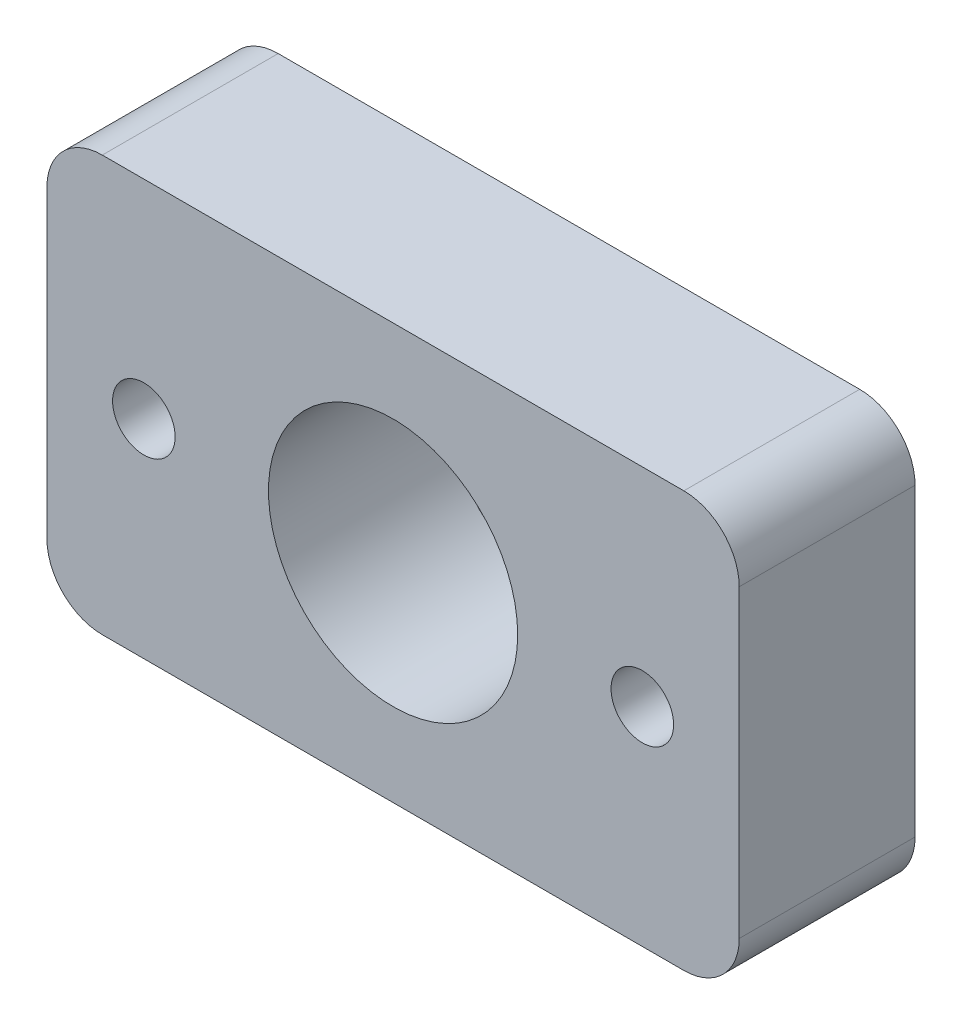
SolidWorks part; units mm, degrees
ref_plane "Front Plane" through (0, 0, 0) normal (0, 0, 1) x (1, 0, 0)
ref_plane "Top Plane" through (0, 0, 0) normal (0, 1, 0) x (1, 0, 0)
ref_plane "Right Plane" through (0, 0, 0) normal (1, 0, 0) x (0, 0, -1)
sketch "Sketch1" plane through (0, 0, 0) normal (0, 0, 1) x (1, 0, 0)
  line L1 (0, 0) -> (25, 0)
  line L2 (0, 0) -> (0, -15)
  line L3 (0, -15) -> (25, -15)
  line L4 (25, 0) -> (25, -15)
  circle A0 centre (12.5, -7.5) radius 4.5
  circle A1 centre (3.5, -7.5) radius 1.1303
  circle A2 centre (21.5, -7.5) radius 1.1303
  circle A3 centre (3.5, -7.5) radius 2.3241 construction
  point P7 (12.5, 0)
  point P9 (25, -7.5)
  dimension "D1" = 9
  dimension "D3" = 2.2606
  dimension "D7" = 4.6482
  dimension "D2" = 25
  dimension "D4" = 18
  dimension "D5" = 3.5
  dimension "D6" = 15
extrude "Boss-Extrude1" add sketch "Sketch1" along normal blind 6.35
hole_wizard "#4-40 Tapped Hole1" positions "3DSketch1" profile "Sketch2" tap size "#4-40" standard "ANSI Inch" end condition through all
sketch3d "3DSketch1"
  line L0 (21.5, -7.5, 6.35) -> (21.5, -7.5, 0) construction
  line L1 (3.5, -7.5, 6.35) -> (3.5, -7.5, 0) construction
  point P0 (21.5, -7.5, 6.35)
  point P4 (3.5, -7.5, 6.35)
sketch "Sketch2" plane through (21.5, -7.5, 6.35) normal (1, 0, 0) x (0, -1, 0)
  line L0 (0, 0) -> (0, 6.35)
  line L1 (0, 6.35) -> (1.1303, 6.35)
  line L2 (1.1303, 6.35) -> (1.1303, 0)
  line L5 (1.1303, 0) -> (0, 0)
  line L11 (0, -6.35) -> (0, 107.95) construction
  dimension "Thru Tap Drill Dia." = 2.2606
  dimension "Thru Tap Drill Depth" = 6.35
cosmetic thread "Hole Thread1" parameters "D2"=2.8448
cosmetic thread "Hole Thread2" parameters "D2"=2.8448
fillet "Fillet1" radius 2 4 edges at (0, -15, 3.175) (0, 0, 3.175) (25, -15, 3.175) (25, 0, 3.175)
equation "\"D5@Sketch1\"=(\"D2@Sketch1\"-\"D4@Sketch1\")/2"
